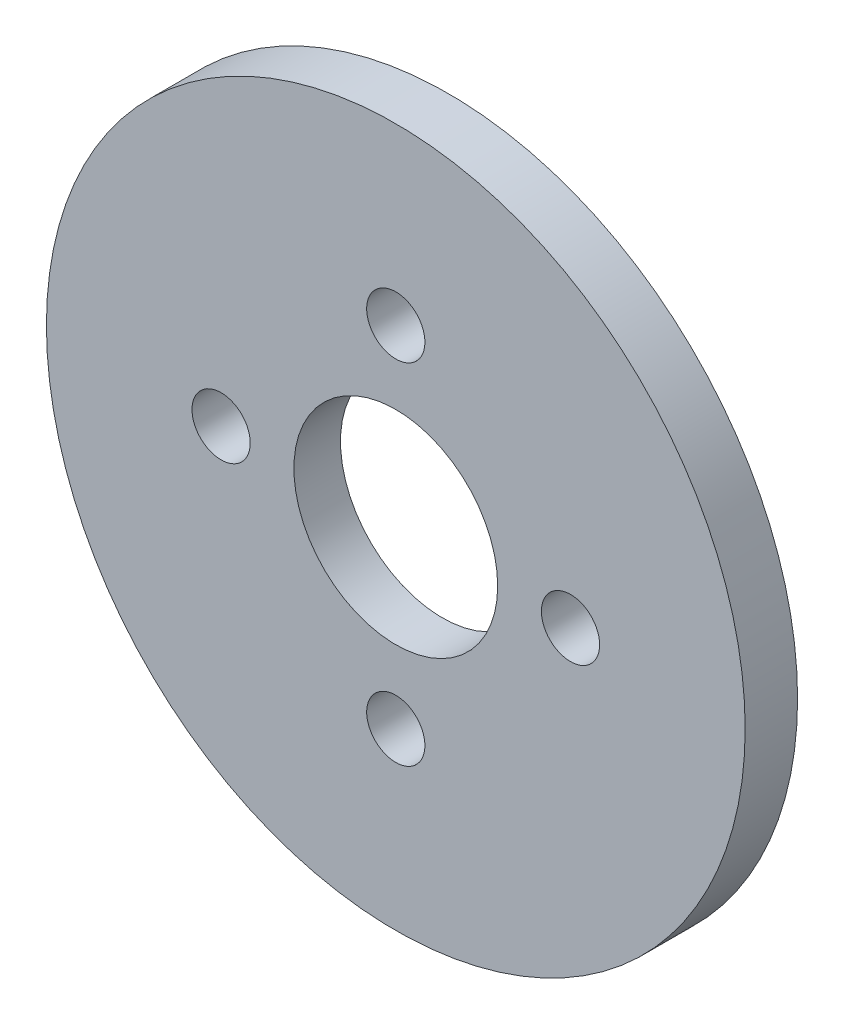
SolidWorks part; units mm, degrees
ref_plane "前视基准面" through (0, 0, 0) normal (0, 0, 1) x (1, 0, 0)
ref_plane "上视基准面" through (0, 0, 0) normal (0, 1, 0) x (1, 0, 0)
ref_plane "右视基准面" through (0, 0, 0) normal (1, 0, 0) x (0, 0, -1)
sketch "草图1" plane through (0, 0, 0) normal (0, 0, 1) x (1, 0, 0)
  circle A0 centre (0, 0) radius 8.75
  circle A1 centre (0, 0) radius 30
  dimension "D1" = 17.5
  dimension "D2" = 60
extrude "凸台-拉伸1" add sketch "草图1" along normal blind 4
sketch "草图4" plane through (0, 0, 0) normal (0, 1, 0) x (1, 0, 0)
  line L0 (-30, 0) -> (-30, 0.5)
  line L1 (-30, 0.5) -> (-20, 0.5)
  line L2 (-20, 0.5) -> (-18, 0)
  line L3 (30, 0) -> (-30, 0) construction
  line L4 (-18, 0) -> (-30, 0)
  line L5 (0, 0) -> (0, 8.6215) construction
  dimension "D1" = 0.5
  dimension "D2" = 12
  dimension "D3" = 10
revolve "旋转1" add sketch "草图4" angle 360 about L5
hole_wizard "M6 螺纹孔1" positions "草图2" profile "草图3" tap size "M6" standard "GB" end condition through all
sketch "草图2" plane through (0, 0, 4) normal (0, 0, 1) x (1, 0, 0)
  line L0 (0, 15) -> (0, 0) construction
  line L1 (0, 0) -> (15, 0) construction
  line L3 (0, -15) -> (0, 0) construction
  line L4 (0, 0) -> (-15, 0) construction
  point P0 (0, 15)
  point P2 (15, 0)
  point P4 (0, -15)
  point P6 (-15, 0)
  dimension "D1" = 15
sketch "草图3" plane through (0, 15, 4) normal (1, 0, 0) x (0, -1, 0)
  line L0 (0, 0) -> (0, 4.5)
  line L1 (0, 4.5) -> (2.5, 4.5)
  line L2 (2.5, 4.5) -> (2.5, 0)
  line L5 (2.5, 0) -> (0, 0)
  line L11 (0, -6.35) -> (0, 107.95) construction
  dimension "通孔螺纹孔钻头直径" = 5
  dimension "通孔螺纹孔钻头深度" = 4.5
cosmetic thread "孔螺蚊线1"
cosmetic thread "孔螺蚊线2"
cosmetic thread "孔螺蚊线3"
cosmetic thread "孔螺蚊线4"
